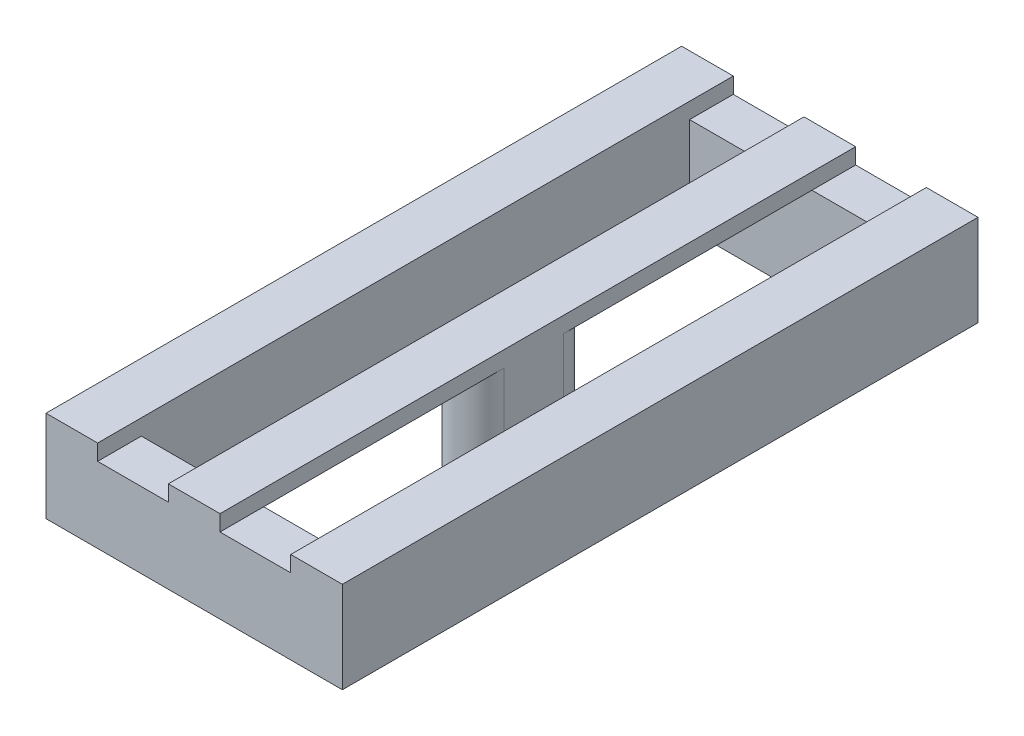
SolidWorks part; units mm, degrees
material "ABS"
ref_plane "Front Plane" through (0, 0, 0) normal (0, 0, 1) x (1, 0, 0)
ref_plane "Top Plane" through (0, 0, 0) normal (0, 1, 0) x (1, 0, 0)
ref_plane "Right Plane" through (0, 0, 0) normal (1, 0, 0) x (0, 0, -1)
sketch "Sketch1" plane through (0, 0, 0) normal (0, 0, 1) x (1, 0, 0)
  line L0 (-3.73, 0) -> (3.73, 0)
  line L1 (3.73, 0) -> (3.73, 3.1)
  line L2 (3.73, 3.1) -> (2.43, 3.1)
  line L3 (2.43, 3.1) -> (2.43, 1.9)
  line L4 (2.43, 1.9) -> (0.65, 1.9)
  line L5 (0.65, 1.9) -> (0.65, 3.1)
  line L6 (0.65, 3.1) -> (-0.65, 3.1)
  line L7 (-0.65, 3.1) -> (-0.65, 1.9)
  line L8 (-0.65, 1.9) -> (-2.43, 1.9)
  line L9 (-2.43, 1.9) -> (-2.43, 3.1)
  line L10 (-2.43, 3.1) -> (-3.73, 3.1)
  line L11 (-3.73, 3.1) -> (-3.73, 0)
  point P9 (0, 0)
  dimension "D1" = 7.46
  dimension "D2" = 1.3
  dimension "D3" = 3.1
  dimension "D4" = 1.9
extrude "Boss-Extrude1" add sketch "Sketch1" against normal blind 16
sketch "Sketch2" plane through (0, 1.9, 0) normal (0, 1, 0) x (1, 0, 0)
  line L0 (2.43, 1.1) -> (2.43, 14.9)
  line L1 (2.43, 14.9) -> (0.65, 14.9)
  line L2 (0.65, 14.9) -> (0.65, 1.1)
  line L3 (0.65, 1.1) -> (2.43, 1.1)
  line L4 (0.65, 0) -> (2.43, 0)
  line L5 (2.43, 0) -> (2.43, 16)
  line L6 (2.43, 16) -> (0.65, 16)
  line L7 (0.65, 16) -> (0.65, 0)
  line L8 (0.65, 0) -> (2.43, 0) construction
  line L9 (2.43, 0) -> (2.43, 16) construction
  line L10 (2.43, 16) -> (0.65, 16) construction
  line L11 (0.65, 16) -> (0.65, 0) construction
  dimension "D2" = 1.1
  dimension "D3" = 1.1
  dimension "D1" = 0
extrude "Cut-Extrude3" cut sketch "Sketch2" against normal through all
mirror "Mirror1" about plane through (0, 0, 0) normal (1, 0, 0) of "Cut-Extrude3"
sketch "Sketch3" plane through (0, 0, 0) normal (0, -1, 0) x (1, 0, 0)
  line L0 (0.65, -1.1) -> (-0.65, -1.1)
  line L1 (-0.65, -1.1) -> (-0.65, -14.9)
  line L2 (-0.65, -14.9) -> (0.65, -14.9)
  line L3 (0.65, -14.9) -> (0.65, -1.1)
extrude "Cut-Extrude4" cut sketch "Sketch3" against normal blind 2.8
ref_plane "Plane1" through (0, 0, -7.9) normal (0, 0, 1) x (1, 0, 0)
sketch "Sketch4" plane through (0, 2.8, 0) normal (0, -1, 0) x (1, 0, 0)
  line L0 (0.65, -7.15) -> (0.65, -8.65)
  line L1 (0.65, -14.9) -> (0.65, -1.1) construction
  line L2 (-0.65, -7.15) -> (-0.65, -8.65)
  line L3 (-0.65, -1.1) -> (-0.65, -14.9) construction
  line L4 (1.98, -7.9) -> (-1.98, -7.9) construction
  arc A2 (0.65, -8.65) -> (-0.65, -8.65) centre (0, -8.65) cw
  arc A3 (0.65, -7.15) -> (-0.65, -7.15) centre (0, -7.15) ccw
  point P10 (0.65, -7.9)
  dimension "D1" = 1.5
extrude "Boss-Extrude2" add sketch "Sketch4" along normal blind 3.4 contours A3 L2 A2 L0
sketch "Sketch5" plane through (0, 0, 0) normal (0, -1, 0) x (1, 0, 0)
  line L0 (3.23, -0.5) -> (3.23, -15.5)
  line L1 (3.23, -15.5) -> (-3.23, -15.5)
  line L2 (-3.23, -15.5) -> (-3.23, -0.5)
  line L3 (-3.23, -0.5) -> (3.23, -0.5)
  line L4 (-3.73, -16) -> (3.73, -16) construction
  line L5 (3.73, -16) -> (3.73, 0) construction
  line L6 (-3.73, 0) -> (3.73, 0) construction
  line L7 (-3.73, -16) -> (-3.73, 0) construction
  dimension "D1" = 0.5
  dimension "D2" = 0.5
  dimension "D3" = 0.5
  dimension "D4" = 0.5
extrude "Boss-Extrude3" add sketch "Sketch5" along normal blind 0.5
sketch "Sketch7" plane through (0, 0, 0) normal (0, 1, 0) x (1, 0, 0)
  line L4 (-2.43, 14.9) -> (-0.65, 14.9)
  line L5 (2.43, 14.9) -> (-2.43, 14.9) construction
  line L6 (-0.65, 14.9) -> (-0.65, 1.1)
  line L7 (-0.65, 1.1) -> (-2.43, 1.1)
  line L8 (-0.65, 0) -> (0.65, 0)
  line L9 (0.65, 0) -> (0.65, 16)
  line L10 (0.65, 16) -> (-0.65, 16)
  line L11 (-0.65, 16) -> (-0.65, 0)
  line L12 (-0.65, 0) -> (0.65, 0) construction
  line L13 (0.65, 0) -> (0.65, 16) construction
  line L14 (0.65, 16) -> (-0.65, 16) construction
  line L15 (-0.65, 16) -> (-0.65, 0) construction
  line L16 (-2.43, 1.1) -> (2.43, 1.1) construction
  line L17 (-2.43, 1.1) -> (-2.43, 14.9)
  dimension "D1" = 0
extrude "Cut-Extrude5" cut sketch "Sketch7" against normal through all
mirror "Mirror2" about plane through (0, 0, 0) normal (1, 0, 0) of "Cut-Extrude5"
sketch "Sketch8" plane through (0, -0.5, 0) normal (0, -1, 0) x (1, 0, 0)
  line L0 (-0.65, -1.1) -> (0.65, -1.1)
  line L1 (0.65, -1.1) -> (0.65, -14.9)
  line L2 (0.65, -14.9) -> (-0.65, -14.9)
  line L3 (-0.65, -14.9) -> (-0.65, -1.1)
extrude "Cut-Extrude6" cut sketch "Sketch8" against normal up to surface (0.1 mm away)
sketch "Sketch9" plane through (0, -0.5, 0) normal (0, -1, 0) x (1, 0, 0)
  line L0 (-0.65, -14.9) -> (0.65, -14.9)
  line L1 (0.65, -14.9) -> (0.65, -8.65)
  line L2 (0.65, -8.65) -> (0.65, -7.15)
  line L3 (-0.65, -7.15) -> (-0.65, -8.65)
  line L4 (0.65, -8.65) -> (0.65, -7.15) construction
  line L5 (-0.65, -7.15) -> (-0.65, -8.65) construction
  line L6 (-0.65, -14.9) -> (-0.65, -8.65)
  arc A1 (-0.65, -8.65) -> (0.65, -8.65) centre (0, -8.65) ccw
  arc A3 (-0.65, -8.65) -> (0.65, -8.65) centre (0, -8.65) ccw
  arc A4 (0.65, -7.15) -> (-0.65, -7.15) centre (0, -7.15) ccw
  arc A5 (-0.65, -8.65) -> (0.65, -8.65) centre (0, -8.65) ccw construction
  arc A6 (0.65, -7.15) -> (-0.65, -7.15) centre (0, -7.15) ccw construction
  dimension "D1" = 0
extrude "Cut-Extrude7" cut sketch "Sketch9" against normal blind 1
mirror "Mirror3" about plane through (0, 0, -7.9) normal (0, 0, 1) of "Cut-Extrude7"
fillet "Fillet1" radius 0.3 4 edges at (-3.23, -0.25, -0.5) (3.23, -0.25, -0.5) (3.23, -0.25, -15.5) (-3.23, -0.25, -15.5)
sketch "Sketch10" plane through (0, 0, 0) normal (0, 0, 1) x (1, 0, 0)
  line L1 (-3.73, 3.1) -> (-3.73, 0) construction
  line L12 (-3.73, 2.3) -> (-3.73, 3.1)
  line L13 (-3.73, 3.1) -> (3.73, 3.1)
  line L14 (3.73, 3.1) -> (3.73, 2.3)
  line L18 (-3.73, 2.3) -> (3.73, 2.3)
  line L37 (3.73, 0) -> (3.73, 3.1) construction
  dimension "D1" = 2.3
extrude "Cut-Extrude9" cut sketch "Sketch10" against normal through all
sketch "Sketch11" plane through (0, 0, -1.1) normal (0, 0, -1) x (-1, 0, 0)
  line L0 (-0.65, 1.9) -> (-0.65, 2.3)
  line L1 (-0.65, 2.3) -> (0.65, 2.3)
  line L2 (0.65, 2.3) -> (0.65, 1.9)
  line L3 (0.65, 1.9) -> (-0.65, 1.9)
extrude "Boss-Extrude4" add sketch "Sketch11" along normal up to surface (13.8 mm away) up to face at (0, 1.4, -14.9)
